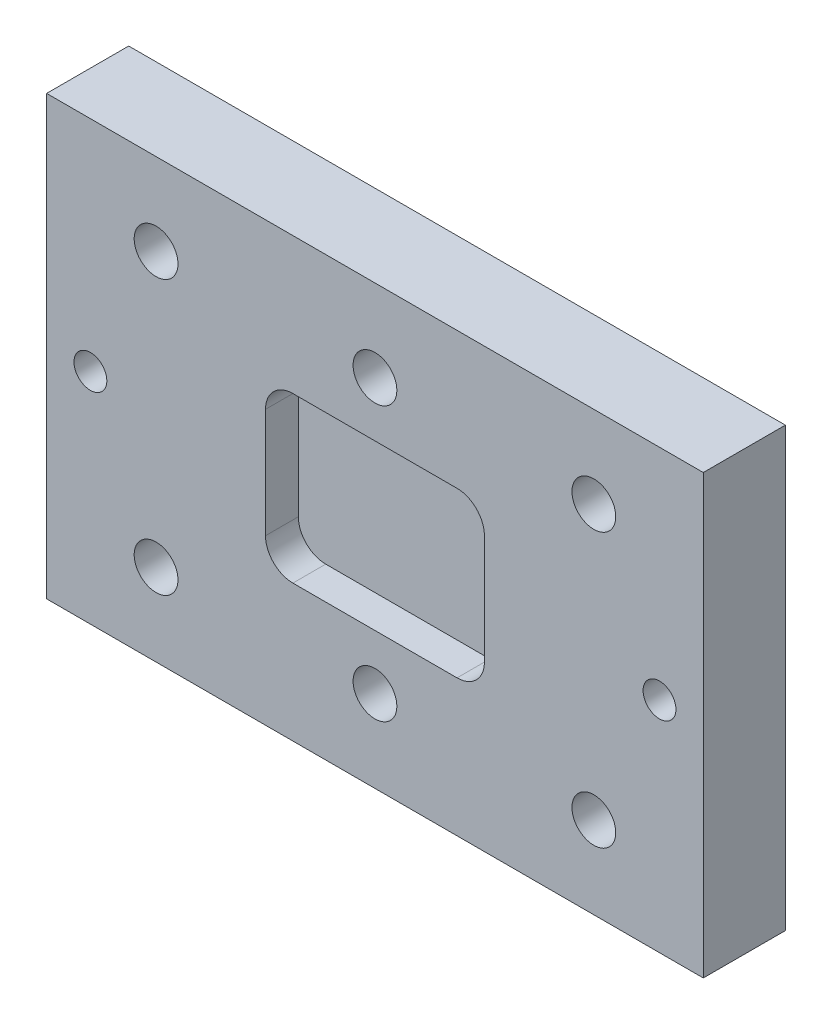
SolidWorks part; units mm, degrees
ref_plane "前视基准面" through (0, 0, 0) normal (0, 0, 1) x (1, 0, 0)
ref_plane "上视基准面" through (0, 0, 0) normal (0, 1, 0) x (1, 0, 0)
ref_plane "右视基准面" through (0, 0, 0) normal (1, 0, 0) x (0, 0, -1)
sketch "草图1" plane through (0, 0, 0) normal (0, 0, 1) x (1, 0, 0)
  line L0 (-60, -40) -> (60, -40)
  line L1 (60, -40) -> (60, 40)
  line L2 (60, 40) -> (-60, 40)
  line L3 (-60, 40) -> (-60, -40)
extrude "凸台-拉伸1" add sketch "草图1" along normal blind 15
ref_plane "基准面1" through (0, 0, 15) normal (0, 0, 1) x (1, 0, 0)
sketch "草图2" plane through (0, 0, 15) normal (0, 0, 1) x (1, 0, 0)
  line L0 (-15, -15) -> (15, -15)
  line L1 (20, -10) -> (20, 10)
  line L2 (15, 15) -> (-15, 15)
  line L3 (-20, 10) -> (-20, -10)
  arc A0 (-20, -10) -> (-15, -15) centre (-15, -10) ccw
  arc A1 (15, -15) -> (20, -10) centre (15, -10) ccw
  arc A2 (20, 10) -> (15, 15) centre (15, 10) ccw
  arc A3 (-15, 15) -> (-20, 10) centre (-15, 10) ccw
extrude "切除-拉伸1" cut sketch "草图2" against normal blind 6
sketch "草图3" plane through (0, 0, 15) normal (0, 0, 1) x (1, 0, 0)
  circle A0 centre (0, 25) radius 4
  circle A1 centre (0, -25) radius 4
  circle A2 centre (40, 25) radius 4
  circle A3 centre (40, -25) radius 4
  circle A4 centre (-40, 25) radius 4
  circle A5 centre (-40, -25) radius 4
extrude "切除-拉伸2" cut sketch "草图3" against normal through all
sketch "草图4" plane through (0, 0, 15) normal (0, 0, 1) x (1, 0, 0)
  circle A0 centre (52, 0) radius 3
  circle A1 centre (-52, 0) radius 3
extrude "切除-拉伸3" cut sketch "草图4" against normal blind 10
